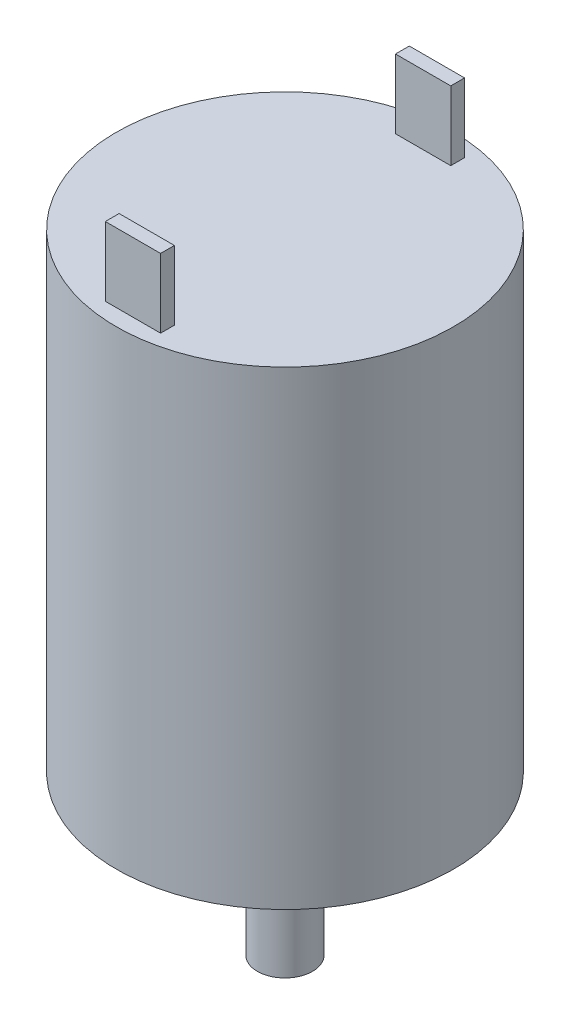
SolidWorks part; units mm, degrees
ref_plane "Front Plane" through (0, 0, 0) normal (0, 0, 1) x (1, 0, 0)
ref_plane "Top Plane" through (0, 0, 0) normal (0, 1, 0) x (1, 0, 0)
ref_plane "Right Plane" through (0, 0, 0) normal (1, 0, 0) x (0, 0, -1)
sketch "Sketch1" plane through (0, 0, 0) normal (0, 0, 1) x (1, 0, 0)
  line L0 (0, 0) -> (12.2, 0)
  line L1 (12.2, 0) -> (12.2, -34)
  line L2 (12.2, -34) -> (2, -34)
  line L3 (2, -34) -> (2, -45.5)
  line L4 (2, -45.5) -> (0, -45.5)
  line L5 (0, -45.5) -> (0, 0) construction
  line L6 (0, 0) -> (0, -45.5)
  dimension "D1" = 12.2
  dimension "D2" = 34
  dimension "D3" = 11.5
  dimension "D4" = 2
revolve "Revolve1" add sketch "Sketch1" angle 360 about L5
sketch "Sketch2" plane through (0, 0, 0) normal (0, 1, 0) x (1, 0, 0)
  line L0 (5.9942, 0) -> (-9.3971, 0) construction
  line L1 (-2, -11) -> (2, -11)
  line L2 (-2, -11) -> (-2, -10)
  line L3 (-2, -10) -> (2, -10)
  line L4 (2, -11) -> (2, -10)
  line L5 (2, 11) -> (2, 10)
  line L6 (-2, 11) -> (-2, 10)
  line L7 (-2, 11) -> (2, 11)
  line L8 (-2, 10) -> (2, 10)
  point P4 (0, -10)
  dimension "D1" = 1
  dimension "D2" = 4
  dimension "D3" = 10
extrude "Boss-Extrude1" add sketch "Sketch2" along normal blind 5
